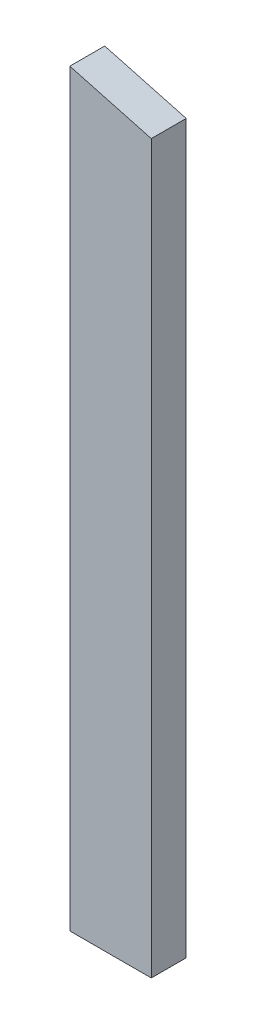
SolidWorks part; units mm, degrees
material "Pine"
ref_plane "Front Plane" through (0, 0, 0) normal (0, 0, 1) x (1, 0, 0)
ref_plane "Top Plane" through (0, 0, 0) normal (0, 1, 0) x (1, 0, 0)
ref_plane "Right Plane" through (0, 0, 0) normal (1, 0, 0) x (0, 0, -1)
sketch "Sketch1" plane through (0, 0, 0) normal (0, 0, 1) x (1, 0, 0)
  line L0 (-108.5345, -3.9032) -> (-108.5345, 1464.0363)
  line L1 (-250.7713, 34.1968) -> (-250.7713, 827.2369)
  line L2 (-870.5345, -3.9032) -> (-870.5345, 625.8363)
  line L3 (-972.1345, 737.9573) -> (-972.1345, 834.2968)
  line L4 (-768.9345, 834.2968) -> (-768.9345, 986.6968)
  line L5 (-972.1345, 834.2968) -> (-768.9345, 834.2968)
  line L6 (-528.0858, 1843.9468) -> (-737.1845, 1843.9468)
  line L7 (-968.4148, 728.977) -> (-874.2542, 634.8165)
  line L8 (-737.1845, 1672.0154) -> (-737.1845, 1762.6932)
  line L9 (-520.195, 1875.6968) -> (-756.2345, 1875.6968)
  line L10 (-112.2542, 1473.0165) -> (-511.2148, 1871.977)
  line L11 (-737.1845, 1692.941) -> (-241.631, 1467.6894)
  line L12 (-596.8655, 1608.234) -> (-737.1845, 983.1768)
  line L13 (-763.9746, 985.3593) -> (-224.4471, 839.8687)
  line L14 (-761.4898, 1669.1128) -> (-638.6318, 1613.2683)
  line L15 (-631.4955, 1598.9249) -> (-768.9345, 986.6968)
  line L16 (-768.9345, 1680.6745) -> (-768.9345, 1862.9968)
  line L17 (-737.1845, 1780.4468) -> (-737.1845, 1843.9468)
  line L18 (-737.1845, 1692.941) -> (-737.1845, 1843.9468) construction
  line L19 (-737.1845, 1692.941) -> (-737.1845, 1762.6932) construction
  line L20 (-838.7845, -3.9032) -> (-838.7845, 834.2968)
  line L21 (-745.0674, 1675.5986) -> (-249.5139, 1450.347) construction
  line L22 (-140.2845, -3.9032) -> (-140.2845, 1456.1455)
  line L23 (-140.2845, 1456.1455) -> (-528.0858, 1843.9468)
  line L24 (-537.8111, 1581.3911) -> (-673.6845, 976.1369)
  line L25 (-768.9345, 966.9663) -> (-229.407, 821.4757)
  line L26 (-737.1845, 1672.0154) -> (-203.7845, 1429.5608)
  line L27 (-528.0858, 1843.9468) -> (-554.3883, 1780.4468)
  line L28 (-140.2845, 1456.1455) -> (-203.7845, 1429.8429)
  line L29 (-775.2845, -3.9032) -> (-775.2845, 834.2968)
  line L30 (-773.8944, 968.3038) -> (-229.407, 821.4757) construction
  line L31 (-203.7845, -3.9032) -> (-203.7845, 1429.8429)
  line L32 (-203.7845, 1429.8429) -> (-554.3883, 1780.4468)
  line L33 (-554.3883, 1780.4468) -> (-737.1845, 1780.4468)
  line L34 (-768.9345, 966.9663) -> (-763.9746, 985.3593)
  line L35 (-737.1845, 1762.6932) -> (-369.5099, 1595.5683)
  line L36 (-673.6845, 1733.8295) -> (-599.2171, 1699.9807) construction
  line L37 (-737.1845, 1692.941) -> (-625.4936, 1642.1724) construction
  line L38 (-538.5586, 1578.0615) -> (-673.6845, 976.1369) construction
  line L39 (-600.5166, 1591.9704) -> (-737.1845, 983.1768) construction
  line L40 (-554.3883, 1780.4468) -> (-673.6845, 1780.4468) construction
  line L41 (-203.7845, 91.3468) -> (-203.7845, 1429.8429) construction
  line L42 (-140.2845, 27.8468) -> (-140.2845, 1456.1455) construction
  line L43 (-775.2845, 91.3468) -> (-775.2845, 625.8363) construction
  line L44 (-838.7845, 27.8468) -> (-838.7845, 625.8363) construction
  line L45 (-203.7845, 91.3468) -> (-775.2845, 91.3468) construction
  line L46 (-140.2845, 27.8468) -> (-838.7845, 27.8468) construction
  line L47 (-940.3845, 745.8481) -> (-851.8036, 657.2672) construction
  line L48 (-843.7807, 739.0468) -> (-806.9023, 702.1685) construction
  line L49 (-843.7807, 739.0468) -> (-673.6845, 739.0468) construction
  line L50 (-940.3845, 802.5468) -> (-737.1845, 802.5468) construction
  line L51 (-940.3845, 745.8481) -> (-940.3845, 802.5468) construction
  line L52 (-843.7807, 739.0468) -> (-843.7807, 739.0468) construction
  line L53 (-673.6845, 1733.8295) -> (-673.6845, 1780.4468) construction
  line L54 (-756.2345, 1692.941) -> (-756.2345, 1792.2779) construction
  line L55 (-756.2345, 1792.2779) -> (-361.627, 1612.9108) construction
  line L56 (-673.6845, 739.0468) -> (-673.6845, 976.1369) construction
  line L57 (-737.1845, 802.5468) -> (-737.1845, 983.1768) construction
  line L58 (-768.9345, 986.6968) -> (-224.4471, 839.8687) construction
  line L59 (-224.4471, 839.8687) -> (-229.407, 821.4757)
  line L60 (-250.7713, -3.9032) -> (-250.7713, 1464.0363) construction
  line L61 (-339.6713, 34.1968) -> (-339.6713, 851.2099)
  line L62 (-339.6713, 34.1968) -> (-339.6713, 827.2369) construction
  line L63 (-108.5345, -3.9032) -> (-248.0476, -3.9032)
  line L68 (-108.5345, -3.9032) -> (-870.5345, -3.9032) construction
  line L69 (-108.5345, -3.9032) -> (-870.5345, -3.9032)
  line L72 (-108.5345, 34.1968) -> (-870.5345, 34.1968)
  arc A0 (-108.5345, 1464.0363) -> (-112.2542, 1473.0165) centre (-121.2345, 1464.0363) ccw
  arc A1 (-511.2148, 1871.977) -> (-520.195, 1875.6968) centre (-520.195, 1862.9968) ccw
  arc A2 (-768.9345, 1862.9968) -> (-756.2345, 1875.6968) centre (-756.2345, 1862.9968) cw
  arc A3 (-768.9345, 1680.6745) -> (-761.4898, 1669.1128) centre (-756.2345, 1680.6745) ccw
  arc A4 (-631.4955, 1598.9249) -> (-638.6318, 1613.2683) centre (-643.8871, 1601.7067) ccw
  arc A5 (-972.1345, 737.9573) -> (-968.4148, 728.977) centre (-959.4345, 737.9573) ccw
  arc A6 (-870.5345, 625.8363) -> (-874.2542, 634.8165) centre (-883.2345, 625.8363) ccw
  arc A7 (-737.1845, 1843.9468) -> (-737.1845, 1843.9468) centre (-737.1845, 1843.9468) cw
  arc A8 (-737.1845, 1692.941) -> (-737.1845, 1692.941) centre (-737.1845, 1692.941) ccw
  arc A12 (-140.2845, 1456.1455) -> (-140.2845, 1456.1455) centre (-140.2845, 1456.1455) ccw
  arc A13 (-528.0858, 1843.9468) -> (-528.0858, 1843.9468) centre (-528.0858, 1843.9468) ccw
  arc A14 (-600.5166, 1591.9704) -> (-625.4936, 1642.1724) centre (-643.8871, 1601.7067) ccw construction
  arc A16 (-203.7845, 1429.8429) -> (-203.7845, 1429.8429) centre (-203.7845, 1429.8429) ccw
  arc A17 (-554.3883, 1780.4468) -> (-554.3883, 1780.4468) centre (-554.3883, 1780.4468) ccw
  arc A18 (-673.6845, 1780.4468) -> (-673.6845, 1780.4468) centre (-673.6845, 1780.4468) cw
  arc A19 (-673.6845, 1733.8295) -> (-673.6845, 1733.8295) centre (-673.6845, 1733.8295) ccw
  arc A20 (-838.7845, 625.8363) -> (-851.8036, 657.2672) centre (-883.2345, 625.8363) ccw construction
  arc A21 (-775.2845, 625.8363) -> (-806.9023, 702.1685) centre (-883.2345, 625.8363) ccw construction
  arc A22 (-843.7807, 739.0468) -> (-843.7807, 739.0468) centre (-843.7807, 739.0468) ccw construction
  arc A23 (-940.3845, 745.8481) -> (-940.3845, 745.8481) centre (-940.3845, 745.8481) ccw construction
  arc A24 (-756.2345, 1692.941) -> (-745.0674, 1675.5986) centre (-737.1845, 1692.941) ccw construction
  point P105 (0, 0)
  point P106 (0, 0)
  dimension "D1" = 12.7
  dimension "D2" = 31.75
  dimension "D3" = 63.5
  dimension "D4" = 19.05
  dimension "D5" = 19.05
  dimension "D8" = 38.1
extrude "Boss-Extrude1" add sketch "Sketch1" along normal blind 38.1 contours L72 L1 L25 L61
